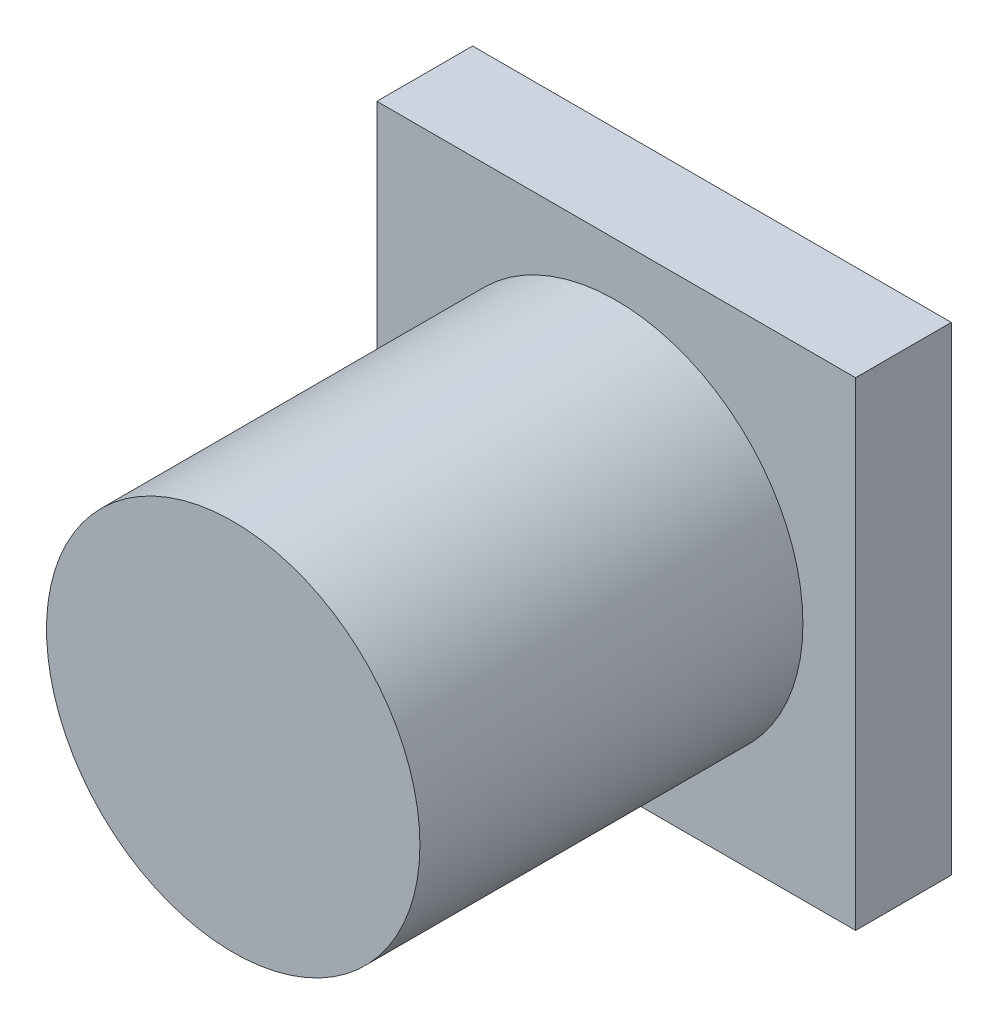
SolidWorks part; units mm, degrees
ref_plane "Alzado" through (0, 0, 0) normal (0, 0, 1) x (1, 0, 0)
ref_plane "Planta" through (0, 0, 0) normal (0, 1, 0) x (1, 0, 0)
ref_plane "Vista lateral" through (0, 0, 0) normal (1, 0, 0) x (0, 0, -1)
sketch "Croquis1" plane through (0, 0, 0) normal (0, 0, 1) x (1, 0, 0)
  line L1 (-5, 5) -> (5, 5)
  line L2 (-5, 5) -> (-5, -5)
  line L3 (-5, -5) -> (5, -5)
  line L4 (5, 5) -> (5, -5)
  line L5 (-5, 5) -> (5, -5) construction
  line L6 (-5, -5) -> (5, 5) construction
  point P0 (0, 0)
  dimension "D1" = 10
  dimension "D2" = 10
extrude "Saliente-Extruir1" add sketch "Croquis1" along normal blind 2
sketch "Croquis2" plane through (0, 0, 2) normal (0, 0, 1) x (1, 0, 0)
  circle A0 centre (0, 0) radius 3.9
  dimension "D1" = 7.8
extrude "Saliente-Extruir2" add sketch "Croquis2" along normal blind 8 contours A0
